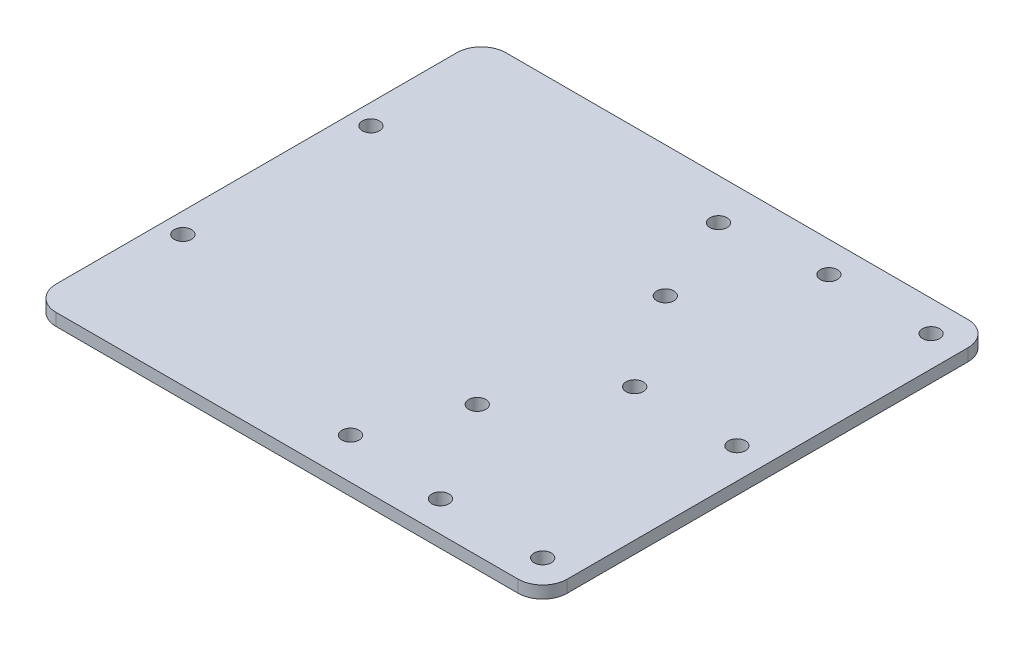
SolidWorks part; units mm, degrees
ref_plane "前视基准面" through (0, 0, 0) normal (0, 0, 1) x (1, 0, 0)
ref_plane "上视基准面" through (0, 0, 0) normal (0, 1, 0) x (1, 0, 0)
ref_plane "右视基准面" through (0, 0, 0) normal (1, 0, 0) x (0, 0, -1)
sketch "草图1" plane through (0, 0, 0) normal (0, 1, 0) x (1, 0, 0)
  line L4 (-109.7882, 42.1105) -> (-109.7882, -55.8895)
  line L5 (-103.7882, -61.8895) -> (9.2118, -61.8895)
  line L6 (15.2118, -55.8895) -> (15.2118, 42.1105)
  line L7 (9.2118, 48.1105) -> (-103.7882, 48.1105)
  line L8 (-65.7882, -25.8895) -> (-65.7882, -29.8895) construction
  line L9 (-65.7882, -29.8895) -> (-69.7882, -29.8895) construction
  line L10 (-69.7882, -29.8895) -> (-97.7882, -29.8895) construction
  arc A0 (15.2118, -55.8895) -> (9.2118, -61.8895) centre (9.2118, -55.8895) cw
  arc A1 (15.2118, 42.1105) -> (9.2118, 48.1105) centre (9.2118, 42.1105) ccw
  arc A2 (-103.7882, 48.1105) -> (-109.7882, 42.1105) centre (-103.7882, 42.1105) ccw
  arc A3 (-103.7882, -61.8895) -> (-109.7882, -55.8895) centre (-103.7882, -55.8895) cw
  point P8 (15.2118, 48.1105)
  point P11 (-109.7882, 48.1105)
  point P14 (-109.7882, -61.8895)
  point P16 (9.2118, 48.1105)
  dimension "D3" = 6
  dimension "D1" = 110
  dimension "D2" = 125
  dimension "D6" = 32
  dimension "D8" = 28
extrude "凸台-拉伸1" add sketch "草图1" along normal blind 3
sketch "草图2" plane through (0, 3, 0) normal (0, 1, 0) x (1, 0, 0)
  line L0 (15.2118, -55.8895) -> (15.2118, 42.1105) construction
  line L2 (7.7118, -6.8895) -> (-17.2882, -6.8895) construction
  line L3 (-17.2882, -6.8895) -> (-17.2882, -54.3895) construction
  circle A0 centre (-17.2882, -54.3895) radius 2.1
  circle A1 centre (7.7118, -54.3895) radius 2.1
  circle A2 centre (-17.2882, -6.8895) radius 2.1
  circle A3 centre (7.7118, -6.8895) radius 2.1
  circle A4 centre (-17.2882, 40.6105) radius 2.1
  circle A5 centre (7.7118, 40.6105) radius 2.1
  point P4 (7.7118, -54.3895)
  dimension "D1" = 4.2
  dimension "D2" = 4.2
  dimension "D3" = 47.5
  dimension "D4" = 25
  dimension "D6" = 7.5
  dimension "D5" = 3
extrude "切除-拉伸1" cut sketch "草图2" against normal through all
sketch "草图3" plane through (0, 3, 0) normal (0, 1, 0) x (1, 0, 0)
  line L0 (-109.7882, 42.1105) -> (-109.7882, -55.8895) construction
  line L1 (-104.7882, 16.1105) -> (-32.7882, 16.1105) construction
  line L2 (-104.7882, 16.1105) -> (-104.7882, -29.8895) construction
  line L3 (-104.7882, -29.8895) -> (-32.7882, -29.8895) construction
  line L4 (-32.7882, 16.1105) -> (-32.7882, -29.8895) construction
  line L5 (-104.7882, 16.1105) -> (-32.7882, -29.8895) construction
  line L6 (-104.7882, -29.8895) -> (-32.7882, 16.1105) construction
  circle A0 centre (-104.7882, -29.8895) radius 2.1
  circle A1 centre (-104.7882, 16.1105) radius 2.1
  circle A2 centre (-32.7882, 16.1105) radius 2.1
  circle A3 centre (-32.7882, -29.8895) radius 2.1
  point P0 (-68.7882, -6.8895)
  point P7 (-109.7882, -6.8895)
  dimension "D4" = 4.2
  dimension "D1" = 46
  dimension "D2" = 72
  dimension "D3" = 5
extrude "切除-拉伸2" cut sketch "草图3" against normal through all
sketch "草图4" plane through (0, 3, 0) normal (0, 1, 0) x (1, 0, 0)
  line L0 (-41.7882, -51.8895) -> (-41.7882, 38.1105) construction
  line L1 (-109.7882, 42.1105) -> (-109.7882, -55.8895) construction
  circle A0 centre (-41.7882, -51.8895) radius 2.1
  circle A1 centre (-41.7882, 38.1105) radius 2.1
  point P4 (-41.7882, -6.8895)
  point P5 (-109.7882, -6.8895)
  dimension "D3" = 4.2
  dimension "D4" = 4.2
  dimension "D1" = 68
  dimension "D2" = 90
extrude "切除-拉伸3" cut sketch "草图4" against normal through all and the other way through all
